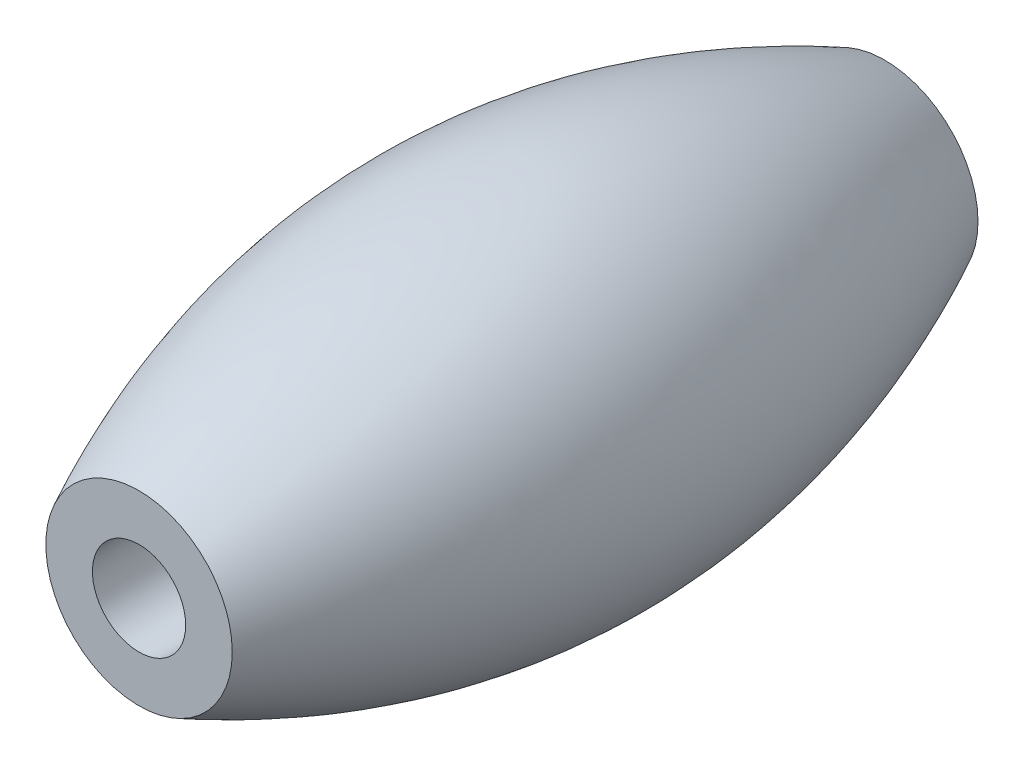
SolidWorks part; units mm, degrees
ref_plane "Front Plane" through (0, 0, 0) normal (0, 0, 1) x (1, 0, 0)
ref_plane "Top Plane" through (0, 0, 0) normal (0, 1, 0) x (1, 0, 0)
ref_plane "Right Plane" through (0, 0, 0) normal (1, 0, 0) x (0, 0, -1)
ref_plane "Plane1" through (0, 0, 16) normal (0, 0, 1) x (1, 0, 0)
ref_plane "Plane2" through (0, 0, -16) normal (0, 0, 1) x (1, 0, 0)
sketch "Sketch1" plane through (0, 0, 0) normal (0, 0, 1) x (1, 0, 0)
  circle A0 centre (0, 0) radius 8
  dimension "D1" = 16
sketch "Sketch2" plane through (0, 0, 16) normal (0, 0, 1) x (1, 0, 0)
  circle A0 centre (0, 0) radius 4
  dimension "D1" = 8
sketch "Sketch3" plane through (0, 0, -16) normal (0, 0, 1) x (1, 0, 0)
  circle A0 centre (0, 0) radius 4
  circle A1 centre (0, 0) radius 4 construction
loft "Loft1" add profiles "Sketch2", "Sketch1", "Sketch3"
sketch "Sketch4" plane through (0, 0, 16) normal (0, 0, 1) x (1, 0, 0)
  circle A0 centre (0, 0) radius 2
  dimension "D1" = 4
extrude "Cut-Extrude1" cut sketch "Sketch4" against normal through all
